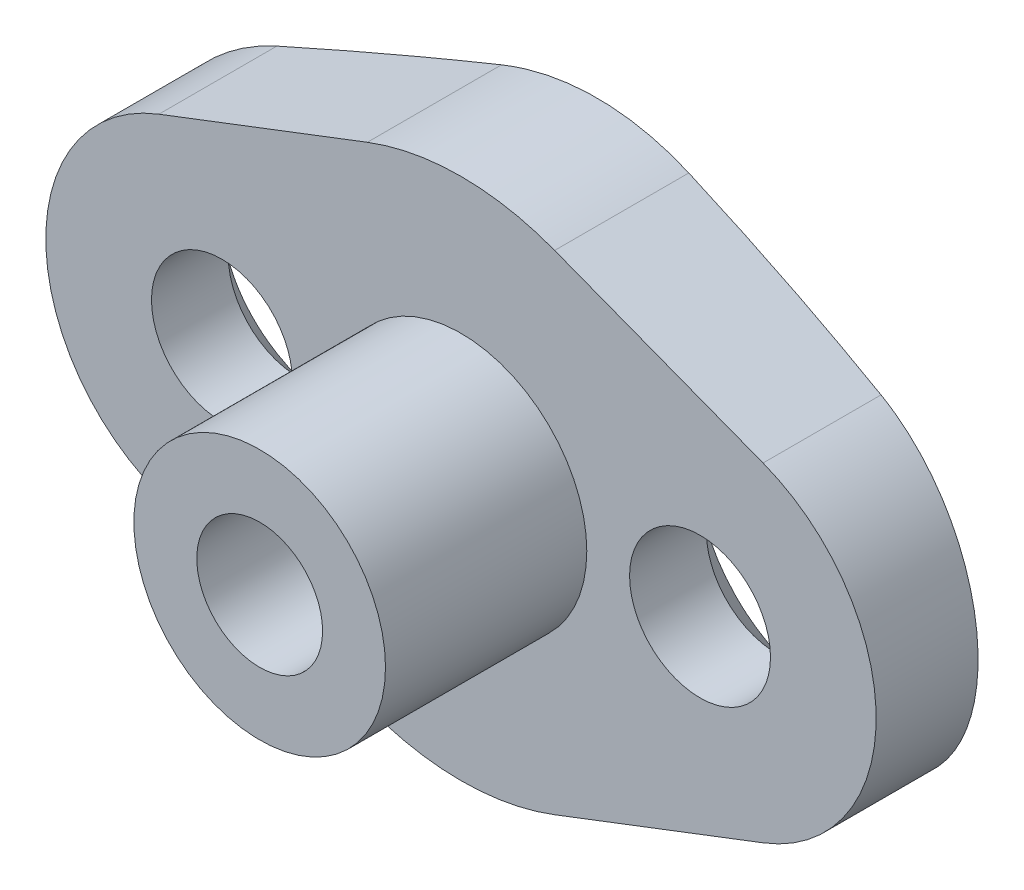
SolidWorks part; units mm, degrees
ref_plane "Front Plane" through (0, 0, 0) normal (0, 0, 1) x (1, 0, 0)
ref_plane "Top Plane" through (0, 0, 0) normal (0, 1, 0) x (1, 0, 0)
ref_plane "Right Plane" through (0, 0, 0) normal (1, 0, 0) x (0, 0, -1)
sketch "Sketch1" plane through (0, 0, 0) normal (0, 0, 1) x (1, 0, 0)
  line L0 (-7.6233, 4.1506) -> (-2.3635, 6.1666)
  line L1 (2.3635, 6.1666) -> (7.6233, 4.1506)
  line L2 (7.6233, -4.1506) -> (2.3635, -6.1666)
  line L3 (-2.3635, -6.1666) -> (-7.6233, -4.1506)
  line L4 (-6.0325, 0) -> (6.0325, 0) construction
  line L5 (-10.4775, 0) -> (10.4775, 0) construction
  circle A0 centre (0, 0) radius 6.604
  circle A1 centre (6.0325, 0) radius 1.778
  circle A2 centre (-6.0325, 0) radius 1.778
  arc A3 (-7.6233, 4.1506) -> (-7.6233, -4.1506) centre (-6.0325, 0) ccw
  arc A4 (7.6233, -4.1506) -> (7.6233, 4.1506) centre (6.0325, 0) ccw
  circle A5 centre (0, 0) radius 1.5875
  dimension "F" = 3.556
  dimension "shaft dia" = 3.175
  dimension "D" = 13.208
  dimension "E" = 12.065
  dimension "B" = 20.955
sketch "Sketch2" plane through (0, 0, 0) normal (0, 1, 0) x (1, 0, 0)
  line L0 (0, 0) -> (0, -8.509) construction
  point P3 (0, -3.429)
  dimension "C" = 8.509
  dimension "G" = 3.429
sketch "Sketch3" plane through (0, 0, 0) normal (0, 0, 1) x (1, 0, 0)
  line L0 (2.3635, 6.1666) -> (7.6233, 4.1506) construction
  line L1 (7.6233, -4.1506) -> (2.3635, -6.1666) construction
  line L2 (-7.6233, 4.1506) -> (-2.3635, 6.1666) construction
  line L3 (-2.3635, -6.1666) -> (-7.6233, -4.1506) construction
  line L4 (2.3635, 6.1666) -> (7.6233, 4.1506)
  line L5 (7.6233, -4.1506) -> (2.3635, -6.1666)
  line L6 (-7.6233, 4.1506) -> (-2.3635, 6.1666)
  line L7 (-2.3635, -6.1666) -> (-7.6233, -4.1506)
  arc A0 (7.6233, -4.1506) -> (7.6233, 4.1506) centre (6.0325, 0) ccw construction
  arc A1 (-7.6233, 4.1506) -> (-7.6233, -4.1506) centre (-6.0325, 0) ccw construction
  arc A2 (7.6233, -4.1506) -> (7.6233, 4.1506) centre (6.0325, 0) ccw
  arc A3 (-7.6233, 4.1506) -> (-7.6233, -4.1506) centre (-6.0325, 0) ccw
  arc A4 (-2.3635, -6.1666) -> (2.3635, -6.1666) centre (0, 0) ccw
  circle A5 centre (-6.0325, 0) radius 1.778
  circle A6 centre (-6.0325, 0) radius 1.778
  circle A7 centre (6.0325, 0) radius 1.778
  circle A8 centre (6.0325, 0) radius 1.778
  circle A9 centre (0, 0) radius 6.604
  arc A10 (2.3635, 6.1666) -> (-2.3635, 6.1666) centre (0, 0) ccw
  circle A11 centre (0, 0) radius 1.5875
  circle A12 centre (0, 0) radius 1.5875 construction
  dimension "D1" = 0
  dimension "D2" = 0
  dimension "D3" = 0
  dimension "D4" = 0
extrude "Extrude1" add sketch "Sketch3" along normal up to vertex (3.429 mm away) up to point (0, 0, 3.429)
sketch "Sketch4" plane through (0, 0, 3.429) normal (0, 0, 1) x (1, 0, 0)
  circle A0 centre (0, 0) radius 1.5875 construction
  circle A1 centre (0, 0) radius 1.5875
  circle A2 centre (0, 0) radius 3.175
  dimension "dd" = 6.35
extrude "Extrude2" add sketch "Sketch4" along normal up to vertex (5.08 mm away) up to point (0, 0, 8.509)
sketch "Sketch5" plane through (0, 0, 0) normal (0, 0, -1) x (-1, 0, 0)
  circle A0 centre (-6.0325, 0) radius 3.556
  circle A1 centre (6.0325, 0) radius 3.556
  dimension "D1" = 7.112
extrude "Cut-Extrude1" cut sketch "Sketch5" against normal through all draft 50
sketch "Sketch6" plane through (0, 0, 0) normal (0, 1, 0) x (1, 0, 0)
  line L0 (10.4775, -0.8573) -> (10.4775, 0.508)
  line L1 (10.4775, 0.508) -> (-10.4775, 0.508)
  line L2 (-10.4775, 0.508) -> (-10.4775, -0.8572)
  line L3 (7.6233, 0) -> (10.4775, 0) construction
  arc A0 (-10.4775, -0.8572) -> (10.4775, -0.8573) centre (0, -64.4578) cw
  dimension "D1" = 0.508
  dimension "D2" = 0.8573
extrude "Cut-Extrude2" cut sketch "Sketch6" against normal mid plane 76.2
equation "\"D1@Sketch5\" = \"F@Sketch1\"*2"
equation "\"D2@Sketch6\" = \"G@Sketch2\"/4"
